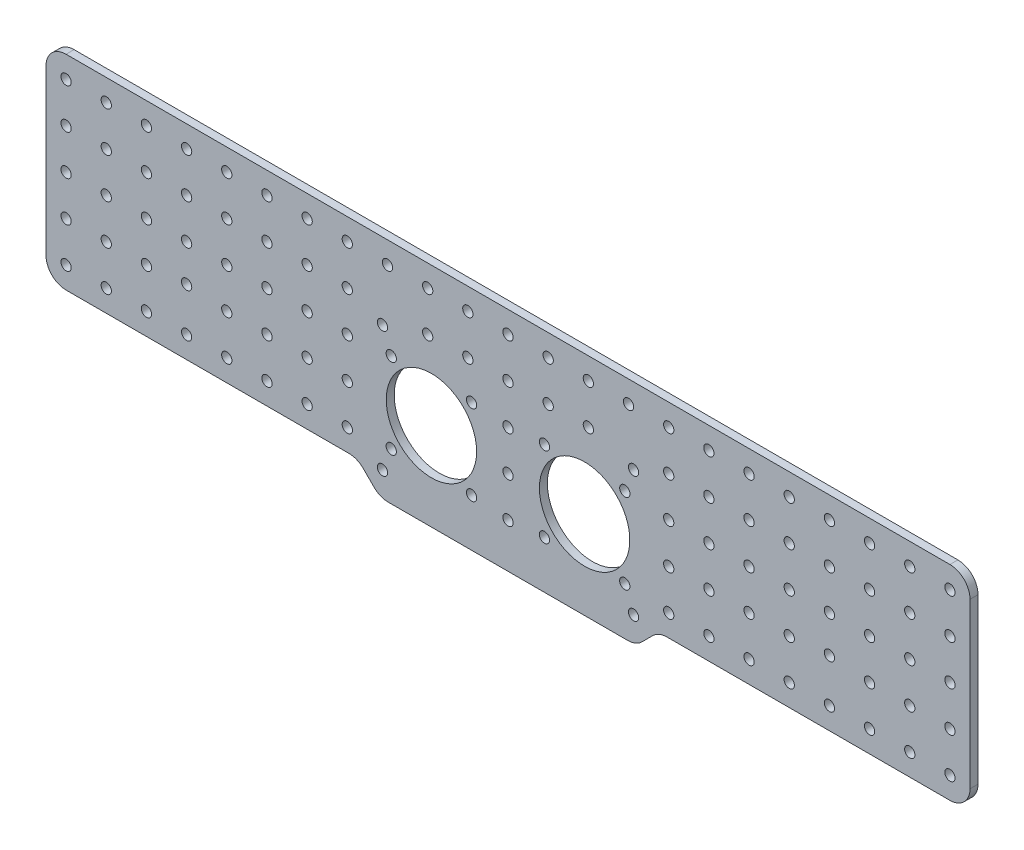
SolidWorks part; units mm, degrees
ref_plane "Front Plane" through (0, 0, 0) normal (0, 0, 1) x (1, 0, 0)
ref_plane "Top Plane" through (0, 0, 0) normal (0, 1, 0) x (1, 0, 0)
ref_plane "Right Plane" through (0, 0, 0) normal (1, 0, 0) x (0, 0, -1)
sketch "Sketch1" plane through (0, 0, 0) normal (0, 0, 1) x (1, 0, 0)
  line L0 (-184, -10.175) -> (184, -10.175) construction
  line L1 (184, 45.175) -> (-184, 45.175)
  line L2 (184, 45.175) -> (184, -45.175)
  line L3 (184, -45.175) -> (-184, -45.175)
  line L4 (-184, 45.175) -> (-184, -45.175)
  line L5 (184, 45.175) -> (-184, -45.175) construction
  line L6 (184, -45.175) -> (-184, 45.175) construction
  line L7 (0, 0) -> (0, -50000) construction
  line L8 (-184, 42) -> (49816, 42) construction
  line L9 (-128, 8.925) -> (-30.5044, 8.925) construction
  line L10 (-128, -29.275) -> (-30.5044, -29.275) construction
  line L11 (-127.8953, -58.1749) -> (-83.2354, -58.0775) construction
  line L12 (50, -35.175) -> (-50, -35.175) construction
  line L13 (50, -35.175) -> (50, 14.825) construction
  line L14 (50, 14.825) -> (-50, 14.825) construction
  line L15 (-50, -35.175) -> (-50, 14.825) construction
  line L16 (50, -35.175) -> (-50, 14.825) construction
  line L17 (50, 14.825) -> (-50, -35.175) construction
  line L18 (-46.5044, 5.825) -> (-14.5044, 5.825) construction
  line L19 (-46.5044, 5.825) -> (-46.5044, -26.175) construction
  line L20 (-46.5044, -26.175) -> (-14.5044, -26.175) construction
  line L21 (-14.5044, 5.825) -> (-14.5044, -26.175) construction
  line L22 (-46.5044, 5.825) -> (-14.5044, -26.175) construction
  line L23 (-46.5044, -26.175) -> (-14.5044, 5.825) construction
  circle A0 centre (-128, -10.175) radius 48 construction
  circle A1 centre (-30.5044, -10.175) radius 18
  circle A3 centre (-128, -10.175) radius 19.1 construction
  circle A4 centre (-30.5044, -10.175) radius 19.1 construction
  arc A5 (-128, 8.925) -> (-128, -29.275) centre (-128, -10.175) ccw construction
  arc A6 (-30.5044, 8.925) -> (-30.5044, -29.275) centre (-30.5044, -10.175) cw construction
  circle A7 centre (-128, -10.175) radius 2.05
  circle A8 centre (128, -10.175) radius 2.05
  circle A9 centre (30.5044, -10.175) radius 18
  circle A10 centre (-50, 14.825) radius 2.05
  circle A11 centre (50, 14.825) radius 2.05
  circle A12 centre (50, -35.175) radius 2.05
  circle A13 centre (-50, -35.175) radius 2.05
  circle A14 centre (-46.5044, 5.825) radius 2.05
  circle A15 centre (-14.5044, 5.825) radius 2.05
  circle A16 centre (-14.5044, -26.175) radius 2.05
  circle A17 centre (-46.5044, -26.175) radius 2.05
  circle A18 centre (46.5044, 5.825) radius 2.05
  circle A19 centre (14.5044, 5.825) radius 2.05
  circle A20 centre (46.5044, -26.175) radius 2.05
  circle A21 centre (14.5044, -26.175) radius 2.05
  point P0 (0, 0)
  point P16 (0, -10.175)
  dimension "D3" = 96
  dimension "D4" = 36
  dimension "D8" = 38.2
  dimension "D10" = 4.1
  dimension "D13" = 4.1
  dimension "D1" = 368
  dimension "D2" = 90.35
  dimension "D5" = 3.175
  dimension "D7" = 56
  dimension "D11" = 50
  dimension "D12" = 100
  dimension "D14" = 32
  dimension "D15" = 32
  dimension "D6" = 55.35
extrude "Boss-Extrude1" add sketch "Sketch1" along normal blind 3.175
sketch "Sketch3" plane through (0, 0, 3.175) normal (0, 0, 1) x (1, 0, 0)
  line L0 (0, 0) -> (0, -50000) construction
  line L1 (0, 0) -> (50000, 0) construction
  line L2 (-82.0903, 42) -> (49917.9097, 42) construction
  line L3 (184, 45.175) -> (-184, 45.175) construction
  line L4 (-151.5131, 36.5) -> (49848.4869, 36.5) construction
  line L5 (-176, 161.8742) -> (-176, -49838.1258) construction
  line L6 (-184, 45.175) -> (-184, -45.175) construction
  line L7 (-159.635, -36.175) -> (49840.365, -36.175) construction
  line L9 (-176, 36.5) -> (-160, 36.5) construction
  line L10 (-176, 36.5) -> (-176, 20.5) construction
  line L11 (-150.701, -33) -> (49849.299, -33) construction
  circle A0 centre (-176, 36.5) radius 2.05
  circle A5 centre (-160, 36.5) radius 2.05
  circle A6 centre (-144, 36.5) radius 2.05
  circle A7 centre (-128, 36.5) radius 2.05
  circle A8 centre (-112, 36.5) radius 2.05
  circle A9 centre (-96, 36.5) radius 2.05
  circle A10 centre (-80, 36.5) radius 2.05
  circle A11 centre (-64, 36.5) radius 2.05
  circle A12 centre (-48, 36.5) radius 2.05
  circle A13 centre (-32, 36.5) radius 2.05
  circle A14 centre (-16, 36.5) radius 2.05
  circle A15 centre (0, 36.5) radius 2.05
  circle A16 centre (16, 36.5) radius 2.05
  circle A17 centre (32, 36.5) radius 2.05
  circle A18 centre (48, 36.5) radius 2.05
  circle A19 centre (64, 36.5) radius 2.05
  circle A20 centre (80, 36.5) radius 2.05
  circle A21 centre (96, 36.5) radius 2.05
  circle A22 centre (112, 36.5) radius 2.05
  circle A23 centre (128, 36.5) radius 2.05
  circle A24 centre (144, 36.5) radius 2.05
  circle A25 centre (160, 36.5) radius 2.05
  circle A26 centre (176, 36.5) radius 2.05
  circle A27 centre (-160, 20.5) radius 2.05
  circle A28 centre (-144, 20.5) radius 2.05
  circle A29 centre (-128, 20.5) radius 2.05
  circle A30 centre (-112, 20.5) radius 2.05
  circle A31 centre (-96, 20.5) radius 2.05
  circle A32 centre (-80, 20.5) radius 2.05
  circle A33 centre (-64, 20.5) radius 2.05
  circle A34 centre (-48, 20.5) radius 2.05 construction
  circle A35 centre (-32, 20.5) radius 2.05
  circle A36 centre (-16, 20.5) radius 2.05
  circle A37 centre (0, 20.5) radius 2.05
  circle A38 centre (16, 20.5) radius 2.05
  circle A39 centre (32, 20.5) radius 2.05
  circle A40 centre (48, 20.5) radius 2.05 construction
  circle A41 centre (64, 20.5) radius 2.05
  circle A42 centre (80, 20.5) radius 2.05
  circle A43 centre (96, 20.5) radius 2.05
  circle A44 centre (112, 20.5) radius 2.05
  circle A45 centre (128, 20.5) radius 2.05
  circle A46 centre (144, 20.5) radius 2.05
  circle A47 centre (160, 20.5) radius 2.05
  circle A48 centre (176, 20.5) radius 2.05
  circle A49 centre (-160, 4.5) radius 2.05
  circle A50 centre (-144, 4.5) radius 2.05
  circle A51 centre (-128, 4.5) radius 2.05
  circle A52 centre (-112, 4.5) radius 2.05
  circle A53 centre (-96, 4.5) radius 2.05
  circle A54 centre (-80, 4.5) radius 2.05
  circle A55 centre (-64, 4.5) radius 2.05
  circle A56 centre (-48, 4.5) radius 2.05 construction
  circle A57 centre (-32, 4.5) radius 2.05 construction
  circle A58 centre (-16, 4.5) radius 2.05 construction
  circle A59 centre (0, 4.5) radius 2.05
  circle A60 centre (16, 4.5) radius 2.05 construction
  circle A61 centre (32, 4.5) radius 2.05 construction
  circle A62 centre (48, 4.5) radius 2.05 construction
  circle A63 centre (64, 4.5) radius 2.05
  circle A64 centre (80, 4.5) radius 2.05
  circle A65 centre (96, 4.5) radius 2.05
  circle A66 centre (112, 4.5) radius 2.05
  circle A67 centre (128, 4.5) radius 2.05
  circle A68 centre (144, 4.5) radius 2.05
  circle A69 centre (160, 4.5) radius 2.05
  circle A70 centre (176, 4.5) radius 2.05
  circle A71 centre (-160, -11.5) radius 2.05
  circle A72 centre (-144, -11.5) radius 2.05
  circle A73 centre (-128, -11.5) radius 2.05 construction
  circle A74 centre (-112, -11.5) radius 2.05
  circle A75 centre (-96, -11.5) radius 2.05
  circle A76 centre (-80, -11.5) radius 2.05
  circle A77 centre (-64, -11.5) radius 2.05
  circle A78 centre (-48, -11.5) radius 2.05 construction
  circle A79 centre (-32, -11.5) radius 2.05 construction
  circle A80 centre (-16, -11.5) radius 2.05 construction
  circle A81 centre (0, -11.5) radius 2.05
  circle A82 centre (16, -11.5) radius 2.05 construction
  circle A83 centre (32, -11.5) radius 2.05 construction
  circle A84 centre (48, -11.5) radius 2.05 construction
  circle A85 centre (64, -11.5) radius 2.05
  circle A86 centre (80, -11.5) radius 2.05
  circle A87 centre (96, -11.5) radius 2.05
  circle A88 centre (112, -11.5) radius 2.05
  circle A89 centre (128, -11.5) radius 2.05 construction
  circle A90 centre (144, -11.5) radius 2.05
  circle A91 centre (160, -11.5) radius 2.05
  circle A92 centre (176, -11.5) radius 2.05
  circle A93 centre (-160, -27.5) radius 2.05
  circle A94 centre (-144, -27.5) radius 2.05
  circle A95 centre (-128, -27.5) radius 2.05
  circle A96 centre (-112, -27.5) radius 2.05
  circle A97 centre (-96, -27.5) radius 2.05
  circle A98 centre (-80, -27.5) radius 2.05
  circle A99 centre (-64, -27.5) radius 2.05
  circle A100 centre (-48, -27.5) radius 2.05 construction
  circle A101 centre (-32, -27.5) radius 2.05 construction
  circle A102 centre (-16, -27.5) radius 2.05 construction
  circle A103 centre (0, -27.5) radius 2.05
  circle A104 centre (16, -27.5) radius 2.05 construction
  circle A105 centre (32, -27.5) radius 2.05 construction
  circle A106 centre (48, -27.5) radius 2.05 construction
  circle A107 centre (64, -27.5) radius 2.05
  circle A108 centre (80, -27.5) radius 2.05
  circle A109 centre (96, -27.5) radius 2.05
  circle A110 centre (112, -27.5) radius 2.05
  circle A111 centre (128, -27.5) radius 2.05
  circle A112 centre (144, -27.5) radius 2.05
  circle A113 centre (160, -27.5) radius 2.05
  circle A114 centre (176, -27.5) radius 2.05
  circle A137 centre (-176, 20.5) radius 2.05
  circle A138 centre (-176, 4.5) radius 2.05
  circle A139 centre (-176, -11.5) radius 2.05
  circle A140 centre (-176, -27.5) radius 2.05
  dimension "D1" = 3.175
  dimension "D4" = 4.1
  dimension "D2" = 5.5
  dimension "D3" = 8
  dimension "D7" = 16
  dimension "D8" = 16
  dimension "D9" = 16
  dimension "D10" = 22.6274
  dimension "D11" = 5.5
  dimension "D12" = 3.175
  dimension "D5" = 23
  dimension "D6" = 5
extrude "Cut-Extrude1" cut sketch "Sketch3" against normal blind 3.18
sketch "Sketch4" plane through (0, 0, 3.175) normal (0, 0, 1) x (1, 0, 0)
  line L0 (-128.5844, -36.18) -> (49871.4156, -36.18) construction
  line L1 (0, 0) -> (0, -50000) construction
  line L2 (-184, -36.18) -> (-60, -36.18)
  line L3 (-184, 45.175) -> (-184, -45.175) construction
  line L4 (-60, -36.18) -> (-51.005, -45.175)
  line L5 (-184, -45.175) -> (184, -45.175) construction
  line L6 (-51.005, -45.175) -> (-184, -45.175)
  line L7 (-184, -45.175) -> (-184, -36.18)
  line L8 (51.005, -45.175) -> (184, -45.175)
  line L9 (60, -36.18) -> (51.005, -45.175)
  line L10 (184, -36.18) -> (60, -36.18)
  line L11 (184, -45.175) -> (184, -36.18)
  circle A0 centre (-176, -27.5) radius 2.05 construction
  dimension "D1" = 8.68
  dimension "D2" = 60
  dimension "D3" = 45
extrude "Cut-Extrude2" cut sketch "Sketch4" against normal blind 10
fillet "Fillet1" radius 8 8 edges at (184, 45.175, 1.5875) (-184, 45.175, 1.5875) (184, -36.18, 1.5875) (51.005, -45.175, 1.5875) (60, -36.18, 1.5875) (-51.005, -45.175, 1.5875) (-60, -36.18, 1.5875) (-184, -36.18, 1.5875)
equation "\"w\"= 368mm"
equation "\"D1@Sketch1\"=\"w\""
equation "\"border\"= 8mm"
equation "\"h\"= 84mm + \"thick\" * 2"
equation "\"D2@Sketch1\"=\"h\""
equation "\"thick\"= 3.175mm"
equation "\"D5@Sketch1\"=\"thick\""
equation "\"innerMotorDiameter\"= 32mm"
equation "\"D4@Sketch1\"=\"innerMotorDiameter\" + 4mm"
equation "\"outerMotorDiameter\"= 38mm"
equation "\"pitchDiameter\"= 38.2mm"
equation "\"D8@Sketch1\"=\"pitchDiameter\""
equation "\"pathLength\"= 315mm'63 Tooth GoBilda Belt"
equation "\"D9@Sketch1\"=\"pathLength\""
equation "\"sh\"= 4.1mm"
equation "\"D10@Sketch1\"=\"sh\""
equation "\"D1@Boss-Extrude1\"=\"thick\""
equation "\"D1@Sketch3\"=\"thick\""
equation "\"D4@Sketch3\"=\"sh\""
equation "\"D13@Sketch1\"=\"sh\""
equation "\"D2\"= \"thick\""
equation "\"D12@Sketch3\"=\"thick\""
